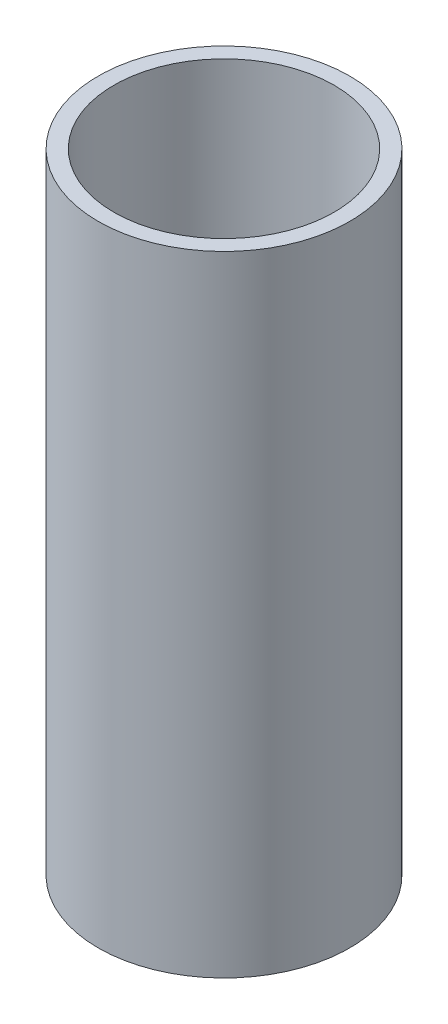
SolidWorks part; units mm, degrees
ref_plane "Front Plane" through (0, 0, 0) normal (0, 0, 1) x (1, 0, 0)
ref_plane "Top Plane" through (0, 0, 0) normal (0, 1, 0) x (1, 0, 0)
ref_plane "Right Plane" through (0, 0, 0) normal (1, 0, 0) x (0, 0, -1)
sketch "Sketch1" plane through (0, 0, 0) normal (0, 1, 0) x (1, 0, 0)
  circle A0 centre (0, 0) radius 14
  circle A1 centre (0, 0) radius 16
  dimension "D1" = 28
  dimension "D2" = 32
extrude "Boss-Extrude1" add sketch "Sketch1" along normal blind 80
